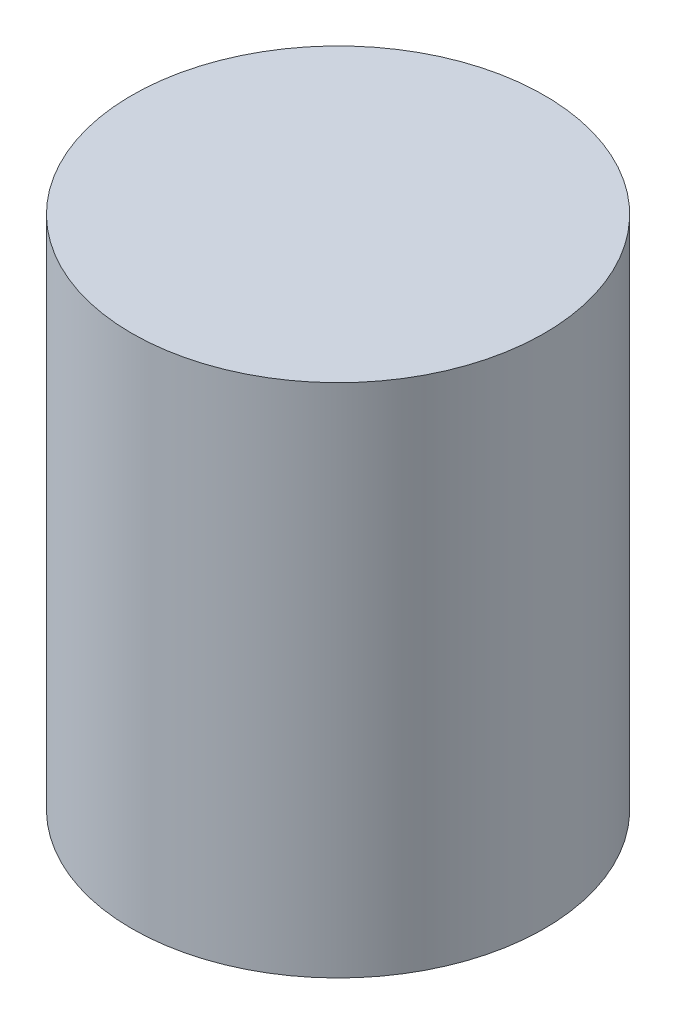
SolidWorks part; units mm, degrees
ref_plane "Front Plane" through (0, 0, 0) normal (0, 0, 1) x (1, 0, 0)
ref_plane "Top Plane" through (0, 0, 0) normal (0, 1, 0) x (1, 0, 0)
ref_plane "Right Plane" through (0, 0, 0) normal (1, 0, 0) x (0, 0, -1)
sketch "Sketch1" plane through (0, 0, 0) normal (0, 1, 0) x (1, 0, 0)
  circle A0 centre (0, 0) radius 20
extrude "Boss-Extrude1" add sketch "Sketch1" along normal blind 50
